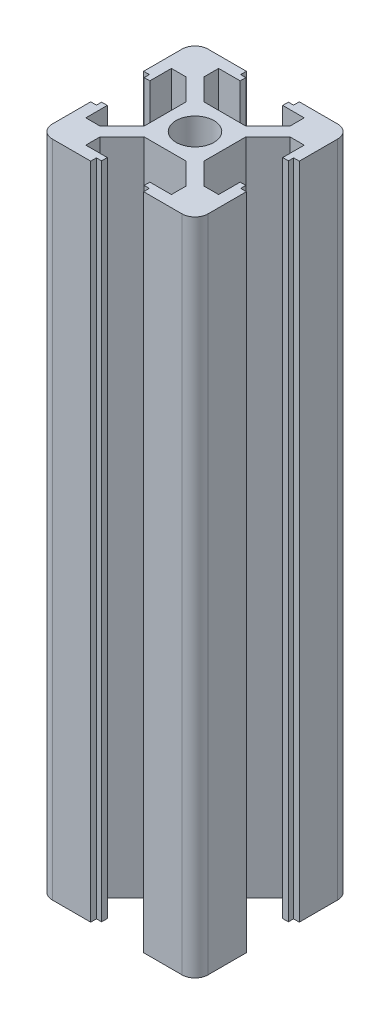
SolidWorks part; units mm, degrees
material "6061-T6 (SS)"
ref_plane "Front Plane" through (0, 0, 0) normal (0, 0, 1) x (1, 0, 0)
ref_plane "Top Plane" through (0, 0, 0) normal (0, 1, 0) x (1, 0, 0)
ref_plane "Right Plane" through (0, 0, 0) normal (1, 0, 0) x (0, 0, -1)
sketch "Sketch1" plane through (0, 0, 0) normal (0, 0, 1) x (1, 0, 0)
  line L0 (0, 63.5) -> (0, -63.5)
  point P4 (0, 0)
  dimension "D1" = 127
other "Boschrexroth BOSCH_30X30_V2(1)"
ref_plane "Plane1" through (0, 63.5, 0) normal (0, -1, 0) x (1, 0, 0)
sketch "Sketch13" plane through (0, 63.5, 0) normal (0, -1, 0) x (1, 0, 0)
  line L0 (0, 0) -> (0, 15) construction
  line L1 (0, 5.8) -> (-4.03, 5.8)
  line L2 (-15, 0) -> (0, 0) construction
  line L3 (-4.03, 5.8) -> (-8.25, 10.02)
  line L4 (-8.25, 10.02) -> (-8.25, 12.8)
  line L5 (-8.25, 12.8) -> (-4.1, 12.8)
  line L6 (-4.1, 12.8) -> (-4.1, 13.9)
  line L7 (-4.1, 13.9) -> (-5.1, 13.9)
  line L8 (-5.1, 13.9) -> (-5.1, 15)
  line L9 (-5.1, 15) -> (-12.5, 15)
  line L10 (-15, 12.5) -> (-15, 5.1)
  line L11 (-15, 5.1) -> (-13.9, 5.1)
  line L12 (-13.9, 5.1) -> (-13.9, 4.1)
  line L13 (-13.9, 4.1) -> (-12.8, 4.1)
  line L14 (-12.8, 4.1) -> (-12.8, 8.25)
  line L15 (-12.8, 8.25) -> (-10.02, 8.25)
  line L16 (-10.02, 8.25) -> (-5.8, 4.03)
  line L17 (-5.8, 4.03) -> (-5.8, 0)
  line L18 (4.1, 13.9) -> (5.1, 13.9)
  line L19 (5.1, 13.9) -> (5.1, 15)
  line L20 (10.02, 8.25) -> (5.8, 4.03)
  line L21 (12.8, 8.25) -> (10.02, 8.25)
  line L22 (12.8, 4.1) -> (12.8, 8.25)
  line L23 (13.9, 4.1) -> (12.8, 4.1)
  line L24 (13.9, 5.1) -> (13.9, 4.1)
  line L25 (15, 5.1) -> (13.9, 5.1)
  line L26 (15, 12.5) -> (15, 5.1)
  line L27 (5.1, 15) -> (12.5, 15)
  line L28 (8.25, 12.8) -> (4.1, 12.8)
  line L29 (8.25, 10.02) -> (8.25, 12.8)
  line L30 (4.03, 5.8) -> (8.25, 10.02)
  line L31 (4.1, 13.9) -> (4.1, 12.8)
  line L32 (4.03, 5.8) -> (0, 5.8)
  line L33 (5.8, 4.03) -> (5.8, 0)
  line L34 (4.1, -13.9) -> (4.1, -12.8)
  line L35 (4.1, -13.9) -> (5.1, -13.9)
  line L36 (5.1, -13.9) -> (5.1, -15)
  line L37 (4.03, -5.8) -> (8.25, -10.02)
  line L38 (8.25, -10.02) -> (8.25, -12.8)
  line L39 (8.25, -12.8) -> (4.1, -12.8)
  line L40 (5.1, -15) -> (12.5, -15)
  line L41 (15, -12.5) -> (15, -5.1)
  line L42 (15, -5.1) -> (13.9, -5.1)
  line L43 (13.9, -5.1) -> (13.9, -4.1)
  line L44 (13.9, -4.1) -> (12.8, -4.1)
  line L45 (12.8, -4.1) -> (12.8, -8.25)
  line L46 (12.8, -8.25) -> (10.02, -8.25)
  line L47 (10.02, -8.25) -> (5.8, -4.03)
  line L48 (5.8, 0) -> (5.8, -4.03)
  line L49 (-13.9, -4.1) -> (-12.8, -4.1)
  line L50 (-13.9, -5.1) -> (-13.9, -4.1)
  line L51 (-15, -5.1) -> (-13.9, -5.1)
  line L52 (-10.02, -8.25) -> (-5.8, -4.03)
  line L53 (-12.8, -8.25) -> (-10.02, -8.25)
  line L54 (-12.8, -4.1) -> (-12.8, -8.25)
  line L55 (-15, -12.5) -> (-15, -5.1)
  line L56 (-5.1, -15) -> (-12.5, -15)
  line L57 (-5.1, -13.9) -> (-5.1, -15)
  line L58 (-4.1, -13.9) -> (-5.1, -13.9)
  line L59 (-4.1, -12.8) -> (-4.1, -13.9)
  line L60 (-8.25, -12.8) -> (-4.1, -12.8)
  line L61 (-8.25, -10.02) -> (-8.25, -12.8)
  line L62 (-4.03, -5.8) -> (-8.25, -10.02)
  line L63 (-5.8, 0) -> (-5.8, -4.03)
  line L64 (-4.03, -5.8) -> (4.03, -5.8)
  line L65 (0, 0) -> (15, 0) construction
  line L66 (0, 0) -> (0, -15) construction
  arc A0 (-12.5, 15) -> (-15, 12.5) centre (-12.5, 12.5) ccw
  arc A1 (-15, -12.5) -> (-12.5, -15) centre (-12.5, -12.5) ccw
  arc A2 (12.5, -15) -> (15, -12.5) centre (12.5, -12.5) ccw
  arc A3 (15, 12.5) -> (12.5, 15) centre (12.5, 12.5) ccw
  circle A4 centre (0, 0) radius 3.65
  point P69 (-15, 15)
  point P72 (-15, -15)
  point P75 (15, -15)
  point P78 (15, 15)
  point P79 (-15, 15)
  point P81 (15, 15)
  point P83 (15, -15)
  point P84 (-15, -15)
  point P86 (0, 0)
  dimension "D15" = 2.5
  dimension "D16" = 7.3
  dimension "D1" = 15
  dimension "D2" = 2.2
  dimension "D3" = 1.1
  dimension "D4" = 1
  dimension "D5" = 8.25
  dimension "D6" = 5.1
  dimension "D7" = 7
  dimension "D8" = 2.78
  dimension "D9" = 15
  dimension "D10" = 15
  dimension "D11" = 4.03
  dimension "D12" = 4.03
  dimension "D13" = 2.5032
  dimension "D14" = 9.2
